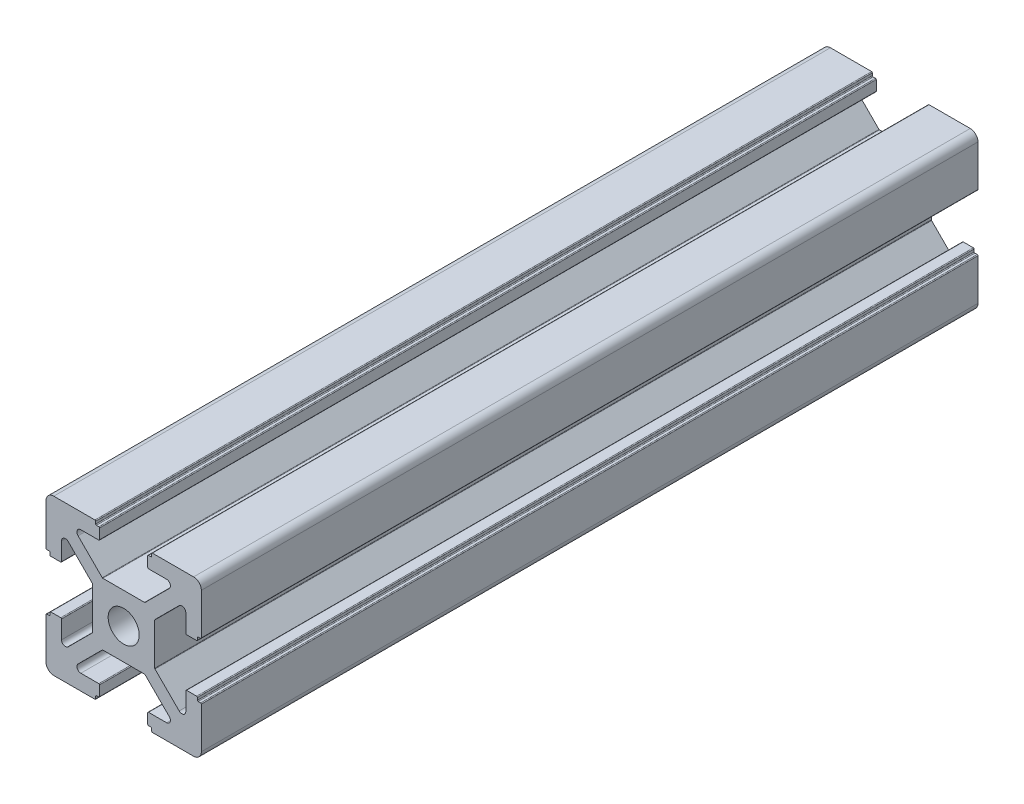
SolidWorks part; units mm, degrees
ref_plane "Plane1" through (0, 0, 0) normal (0, 0, 1) x (1, 0, 0)
ref_plane "Plane2" through (0, 0, 0) normal (0, 1, 0) x (1, 0, 0)
ref_plane "Plane3" through (0, 0, 0) normal (1, 0, 0) x (0, 0, -1)
sketch "Sketch1" plane through (0, 0, 0) normal (0, 0, 1) x (1, 0, 0)
  line L0 (-26.4662, 0) -> (25.1675, 0) construction
  line L1 (0, 16.7588) -> (0, -17.8201) construction
  line L2 (-10, 9) -> (-10, 3.7)
  line L3 (8, -5.5201) -> (8, -3.2)
  line L4 (-4, 0) -> (-4, 2.6858)
  line L5 (-2.6858, 4) -> (2.6858, 4)
  line L6 (4, 0) -> (4, 2.6858)
  line L7 (-4, -4) -> (4, 4) construction
  line L8 (-4, 4) -> (4, -4) construction
  line L9 (-9, 10) -> (-3.7, 10)
  line L10 (-8, 5.5201) -> (-8, 3.2)
  line L11 (10, -9) -> (10, -3.7)
  line L12 (9.6, -3.6) -> (9.9, -3.6)
  line L13 (-10, 10) -> (10, -10) construction
  line L14 (-10, -10) -> (10, 10) construction
  line L15 (9.5, -3.2) -> (9.5, -3.5)
  line L16 (8.1, -3.1) -> (9.4, -3.1)
  line L17 (-5.5201, 8) -> (-3.2, 8)
  line L18 (-7.1464, 5.8737) -> (-4.0293, 2.7565)
  line L19 (-5.8737, 7.1464) -> (-2.7565, 4.0293)
  line L20 (-3.1, 8.1) -> (-3.1, 9.4)
  line L21 (-3.2, 9.5) -> (-3.5, 9.5)
  line L22 (-3.6, 9.6) -> (-3.6, 9.9)
  line L23 (3.1, 8.1) -> (3.1, 9.4)
  line L24 (3.2, 9.5) -> (3.5, 9.5)
  line L25 (3.6, 9.6) -> (3.6, 9.9)
  line L26 (2.7565, 4.0293) -> (5.8737, 7.1464)
  line L27 (4.0293, 2.7565) -> (7.1464, 5.8737)
  line L28 (-8, 8) -> (8, 8) construction
  line L29 (-8, 8) -> (-8, -8) construction
  line L30 (8, 8) -> (8, -8) construction
  line L31 (3.7, 10) -> (9, 10)
  line L32 (-9, 10) -> (9, 10) construction
  line L33 (3.2, 8) -> (5.5201, 8)
  line L34 (-9.5, 3.2) -> (-9.5, 3.5)
  line L35 (-9.6, 3.6) -> (-9.9, 3.6)
  line L36 (-8.1, 3.1) -> (-9.4, 3.1)
  line L37 (-9, -10) -> (9, -10) construction
  line L38 (-10, 9) -> (-10, -9) construction
  line L39 (-8, -8) -> (8, -8) construction
  line L40 (10, 9) -> (10, -9) construction
  line L41 (8.1, 3.1) -> (9.4, 3.1)
  line L42 (9.5, 3.2) -> (9.5, 3.5)
  line L43 (9.6, 3.6) -> (9.9, 3.6)
  line L44 (10, 9) -> (10, 3.7)
  line L45 (8, 5.5201) -> (8, 3.2)
  line L46 (-8.1, -3.1) -> (-9.4, -3.1)
  line L47 (-9.6, -3.6) -> (-9.9, -3.6)
  line L48 (-9.5, -3.2) -> (-9.5, -3.5)
  line L49 (3.2, -8) -> (5.5201, -8)
  line L50 (3.7, -10) -> (9, -10)
  line L51 (4.0293, -2.7565) -> (7.1464, -5.8737)
  line L52 (2.7565, -4.0293) -> (5.8737, -7.1464)
  line L53 (3.6, -9.6) -> (3.6, -9.9)
  line L54 (3.2, -9.5) -> (3.5, -9.5)
  line L55 (3.1, -8.1) -> (3.1, -9.4)
  line L56 (-3.6, -9.6) -> (-3.6, -9.9)
  line L57 (-3.2, -9.5) -> (-3.5, -9.5)
  line L58 (-3.1, -8.1) -> (-3.1, -9.4)
  line L59 (-5.8737, -7.1464) -> (-2.7565, -4.0293)
  line L60 (-7.1464, -5.8737) -> (-4.0293, -2.7565)
  line L61 (-5.5201, -8) -> (-3.2, -8)
  line L62 (-8, -5.5201) -> (-8, -3.2)
  line L63 (-9, -10) -> (-3.7, -10)
  line L64 (-2.6858, -4) -> (2.6858, -4)
  line L65 (-10, -9) -> (-10, -3.7)
  line L66 (-4, 0) -> (-4, -2.6858)
  line L68 (4, 0) -> (4, -2.6858)
  circle A0 centre (0, 0) radius 2
  arc A1 (-10, 9) -> (-9, 10) centre (-9, 9) cw
  arc A2 (10, -3.7) -> (9.9, -3.6) centre (9.9, -3.7) ccw
  arc A3 (-10, -9) -> (-9, -10) centre (-9, -9) ccw construction
  arc A4 (10, 9) -> (9, 10) centre (9, 9) ccw
  arc A5 (-8, -8) -> (-8, -8) centre (-8, -8) ccw
  arc A6 (8, -8) -> (8, -8) centre (8, -8) cw
  arc A7 (8, 8) -> (8, 8) centre (8, 8) ccw
  arc A8 (-8, 8) -> (-8, 8) centre (-8, 8) cw
  arc A9 (-5.5201, 8) -> (-5.8737, 7.1464) centre (-5.5201, 7.5) ccw
  arc A10 (5.5201, 8) -> (5.8737, 7.1464) centre (5.5201, 7.5) cw
  arc A11 (-8, 5.5201) -> (-7.1464, 5.8737) centre (-7.5, 5.5201) cw
  arc A12 (8, 5.5201) -> (7.1464, 5.8737) centre (7.5, 5.5201) ccw
  arc A13 (-3.6, 9.9) -> (-3.7, 10) centre (-3.7, 9.9) ccw
  arc A14 (-3.5, 9.5) -> (-3.6, 9.6) centre (-3.5, 9.6) cw
  arc A15 (-3.2, 9.5) -> (-3.1, 9.4) centre (-3.2, 9.4) cw
  arc A16 (-3.1, 8.1) -> (-3.2, 8) centre (-3.2, 8.1) cw
  arc A17 (3.2, 8) -> (3.1, 8.1) centre (3.2, 8.1) cw
  arc A18 (3.2, 9.5) -> (3.1, 9.4) centre (3.2, 9.4) ccw
  arc A19 (3.5, 9.5) -> (3.6, 9.6) centre (3.5, 9.6) ccw
  arc A20 (3.7, 10) -> (3.6, 9.9) centre (3.7, 9.9) ccw
  arc A21 (-2.6858, 4) -> (-2.7565, 4.0293) centre (-2.6858, 4.1) cw
  arc A22 (-4, 2.6858) -> (-4.0293, 2.7565) centre (-4.1, 2.6858) ccw
  arc A23 (2.6858, 4) -> (2.7565, 4.0293) centre (2.6858, 4.1) ccw
  arc A24 (4.0293, 2.7565) -> (4, 2.6858) centre (4.1, 2.6858) ccw
  arc A25 (-9.5, 3.2) -> (-9.4, 3.1) centre (-9.4, 3.2) ccw
  arc A26 (-9.5, 3.5) -> (-9.6, 3.6) centre (-9.6, 3.5) ccw
  arc A27 (-9.9, 3.6) -> (-10, 3.7) centre (-9.9, 3.7) cw
  arc A28 (-8.1, 3.1) -> (-8, 3.2) centre (-8.1, 3.2) ccw
  arc A29 (8, 3.2) -> (8.1, 3.1) centre (8.1, 3.2) ccw
  arc A30 (9.5, 3.2) -> (9.4, 3.1) centre (9.4, 3.2) cw
  arc A31 (9.5, 3.5) -> (9.6, 3.6) centre (9.6, 3.5) cw
  arc A32 (10, 3.7) -> (9.9, 3.6) centre (9.9, 3.7) cw
  arc A33 (10, -9) -> (9, -10) centre (9, -9) cw construction
  arc A34 (9.5, -3.5) -> (9.6, -3.6) centre (9.6, -3.5) ccw
  arc A35 (9.5, -3.2) -> (9.4, -3.1) centre (9.4, -3.2) ccw
  arc A36 (8, -3.2) -> (8.1, -3.1) centre (8.1, -3.2) cw
  arc A37 (-8.1, -3.1) -> (-8, -3.2) centre (-8.1, -3.2) cw
  arc A38 (-9.9, -3.6) -> (-10, -3.7) centre (-9.9, -3.7) ccw
  arc A39 (-9.5, -3.5) -> (-9.6, -3.6) centre (-9.6, -3.5) cw
  arc A40 (-9.5, -3.2) -> (-9.4, -3.1) centre (-9.4, -3.2) cw
  arc A41 (4.0293, -2.7565) -> (4, -2.6858) centre (4.1, -2.6858) cw
  arc A42 (2.6858, -4) -> (2.7565, -4.0293) centre (2.6858, -4.1) cw
  arc A43 (-4, -2.6858) -> (-4.0293, -2.7565) centre (-4.1, -2.6858) cw
  arc A44 (-2.6858, -4) -> (-2.7565, -4.0293) centre (-2.6858, -4.1) ccw
  arc A45 (3.7, -10) -> (3.6, -9.9) centre (3.7, -9.9) cw
  arc A46 (3.5, -9.5) -> (3.6, -9.6) centre (3.5, -9.6) cw
  arc A47 (3.2, -9.5) -> (3.1, -9.4) centre (3.2, -9.4) cw
  arc A48 (3.2, -8) -> (3.1, -8.1) centre (3.2, -8.1) ccw
  arc A49 (-3.1, -8.1) -> (-3.2, -8) centre (-3.2, -8.1) ccw
  arc A50 (-3.2, -9.5) -> (-3.1, -9.4) centre (-3.2, -9.4) ccw
  arc A51 (-3.5, -9.5) -> (-3.6, -9.6) centre (-3.5, -9.6) ccw
  arc A52 (-3.6, -9.9) -> (-3.7, -10) centre (-3.7, -9.9) cw
  arc A53 (8, -5.5201) -> (7.1464, -5.8737) centre (7.5, -5.5201) cw
  arc A54 (-8, -5.5201) -> (-7.1464, -5.8737) centre (-7.5, -5.5201) ccw
  arc A55 (5.5201, -8) -> (5.8737, -7.1464) centre (5.5201, -7.5) ccw
  arc A56 (-5.5201, -8) -> (-5.8737, -7.1464) centre (-5.5201, -7.5) cw
  arc A57 (10, -9) -> (9, -10) centre (9, -9) cw
  arc A58 (-10, -9) -> (-9, -10) centre (-9, -9) ccw
  point P0 (0, 0)
  point P70 (3.1, 8.75)
  point P72 (-3.6, 10)
  point P75 (-3.6, 9.5)
  point P82 (3.1, 8)
  point P87 (3.6, 9.5)
  point P90 (3.6, 10)
  point P198 (3.6, -10)
  point P199 (3.6, -9.5)
  point P200 (3.1, -8)
  point P201 (-3.6, -9.5)
  point P202 (-3.6, -10)
extrude "Boss-Extrude1" add sketch "Sketch1" along normal blind 100 contours L65 A58 L63 A52 L56 A51 L57 A50 L58 A49 L61 A56 L59 A44 L64 A42 L52 A55 L49 A48 L55 A47 L54 A46 L53 A45 L50 A57 L11 A2 L12 A34 L15 A35 L16 A36 L3 A53 L51 A41 L68 L6 A24 L27 A12 L45 A29 L41 A30 L42 A31
